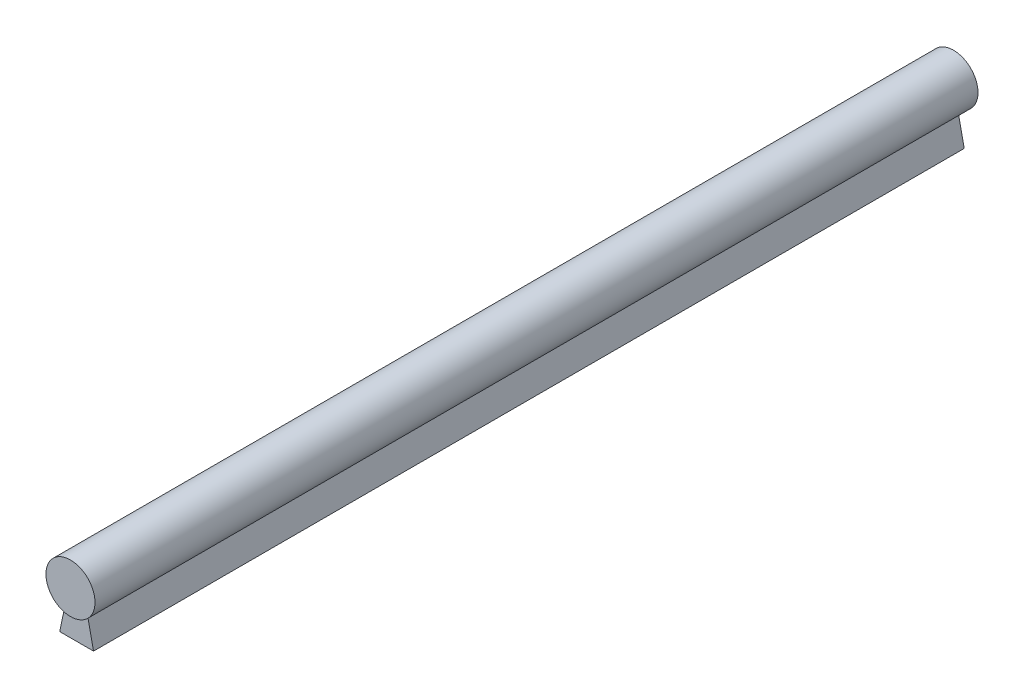
SolidWorks part; units mm, degrees
material "PW50:8:Ar:0:-1:C1:1:2:3:Re:27:"
ref_plane "front" through (0, 0, 0) normal (0, 0, 1) x (1, 0, 0)
ref_plane "top" through (0, 0, 0) normal (0, 1, 0) x (1, 0, 0)
ref_plane "side" through (0, 0, 0) normal (1, 0, 0) x (0, 0, -1)
sketch "Sketch1" plane through (0, 0, 0) normal (0, 0, 1) x (1, 0, 0)
  circle A0 centre (0, 0) radius 12.7
  dimension "D1" = 25.4
extrude "Base-Extrude" add sketch "Sketch1" along normal blind 457.2
ref_plane "Plane4" through (0, 0, 3.175) normal (0, 0, 1) x (1, 0, 0)
sketch "Sketch2" plane through (0, 0, 3.175) normal (0, 0, 1) x (1, 0, 0)
  line L0 (0, 0) -> (0, -25.4) construction
  line L1 (-8.763, -25.4) -> (8.763, -25.4)
  line L2 (8.763, -25.4) -> (5.769, -11.3141)
  line L3 (8.763, -25.4) -> (8.763, -14.2842) construction
  line L4 (-8.763, -25.4) -> (-5.769, -11.3141)
  circle A0 centre (0, 0) radius 12.7 construction
  arc A1 (-5.769, -11.3141) -> (5.769, -11.3141) centre (0, 0) ccw
  point P9 (0, -25.4)
  dimension "D1" = 12
  dimension "D2" = 25.4
  dimension "D3" = 17.526
extrude "Boss-Extrude1" add sketch "Sketch2" along normal blind 450.85
